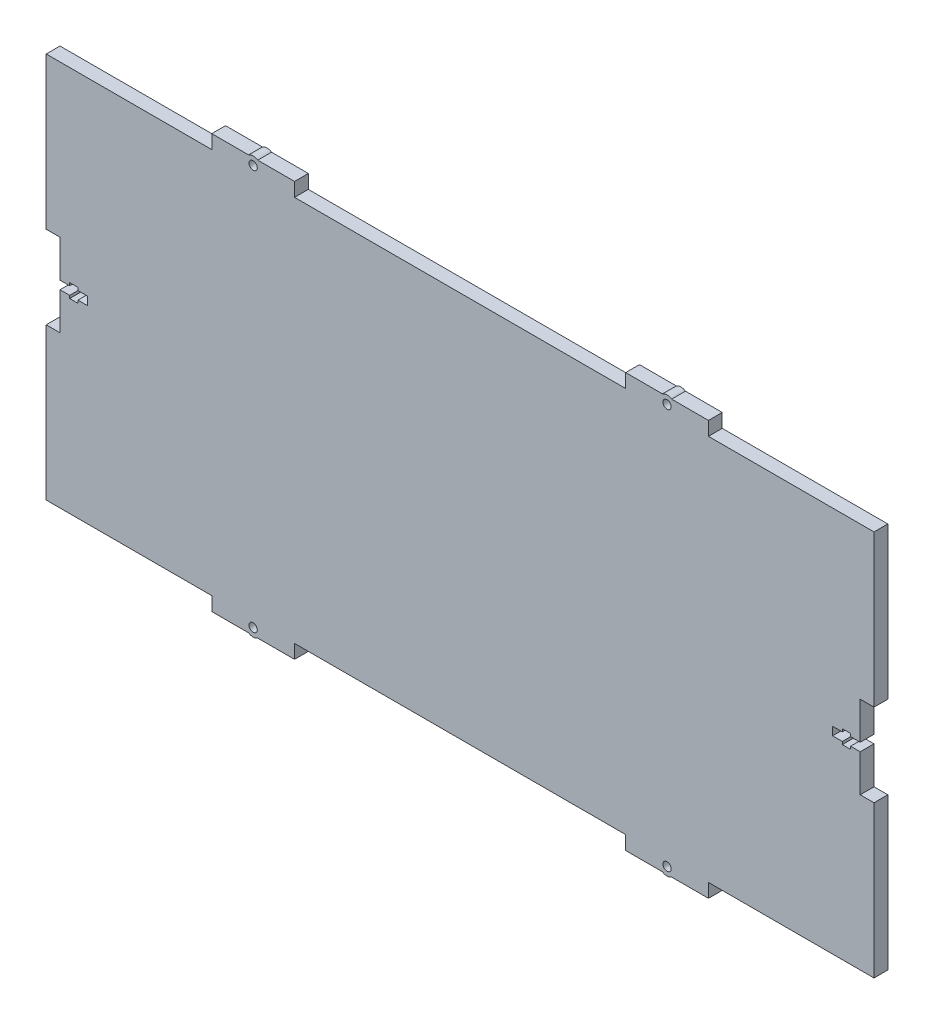
SolidWorks part; units mm, degrees
ref_plane "Plan de face" through (0, 0, 0) normal (0, 0, 1) x (1, 0, 0)
ref_plane "Plan de dessus" through (0, 0, 0) normal (0, 1, 0) x (1, 0, 0)
ref_plane "Plan de droite" through (0, 0, 0) normal (1, 0, 0) x (0, 0, -1)
sketch "Esquisse1" plane through (0, 0, 0) normal (0, 0, 1) x (1, 0, 0)
  line L4 (-160.6231, -51.1462) -> (-105.6231, -51.1462)
  line L5 (-160.6231, -51.1462) -> (-160.6231, 88.8538)
  line L6 (-160.6231, 88.8538) -> (-105.6231, 88.8538)
  line L7 (129.3769, -51.1462) -> (129.3769, 88.8538)
  line L8 (74.3769, -51.1462) -> (74.3769, -56.1462)
  line L10 (74.3769, -56.1462) -> (61.0352, -56.1462)
  line L11 (57.7186, -56.1462) -> (44.3769, -56.1462)
  line L12 (44.3769, -51.1462) -> (44.3769, -56.1462)
  line L13 (-75.6231, -51.1462) -> (-75.6231, -56.1462)
  line L14 (-89.1231, -56.1462) -> (-75.6231, -56.1462)
  line L15 (74.3769, -51.1462) -> (129.3769, -51.1462)
  line L16 (-105.6231, -56.1462) -> (-92.1231, -56.1462)
  line L17 (-105.6231, -51.1462) -> (-105.6231, -56.1462)
  line L19 (74.3769, 93.8538) -> (60.8769, 93.8538)
  line L20 (57.8769, 93.8538) -> (44.3769, 93.8538)
  line L21 (44.3769, 93.8538) -> (44.3769, 88.8538)
  line L22 (-75.6231, 93.8538) -> (-75.6231, 88.8538)
  line L23 (-89.1231, 93.8538) -> (-75.6231, 93.8538)
  line L24 (-15.6231, 104.2463) -> (-15.6231, -104.3766) construction
  line L25 (-105.6231, 93.8538) -> (-92.1231, 93.8538)
  line L26 (-105.6231, 93.8538) -> (-105.6231, 88.8538)
  line L27 (-196.6289, 18.8538) -> (196.6984, 18.8538) construction
  line L28 (74.3769, 93.8538) -> (74.3769, 88.8538)
  line L29 (74.3769, 88.8538) -> (129.3769, 88.8538)
  line L30 (-75.6231, 88.8538) -> (44.3769, 88.8538)
  line L31 (-75.6231, -51.1462) -> (44.3769, -51.1462)
  circle A1 centre (-90.6231, 91.3538) radius 1.5
  arc A2 (-88.9648, 93.8538) -> (-92.2814, 93.8538) centre (-90.6231, 91.3538) ccw
  arc A4 (57.7186, 93.8538) -> (61.0352, 93.8538) centre (59.3769, 91.3538) cw
  circle A6 centre (59.3769, 91.3538) radius 1.5
  arc A8 (57.7186, -56.1462) -> (61.0352, -56.1462) centre (59.3769, -53.6462) ccw
  circle A9 centre (59.3769, -53.6462) radius 1.5
  arc A10 (-88.9648, -56.1462) -> (-92.2814, -56.1462) centre (-90.6231, -53.6462) cw
  circle A11 centre (-90.6231, -53.6462) radius 1.5
  dimension "D1" = 140
extrude "Boss.-Extru.2" add sketch "Esquisse1" along normal blind 5
sketch "Esquisse2" plane through (-160.6231, 0, 0) normal (-1, 0, 0) x (0, 0, 1)
  line L4 (0, 88.8538) -> (0, -51.1462)
  line L5 (0, -51.1462) -> (5, -51.1462)
  line L6 (5, -51.1462) -> (5, 88.8538)
  line L7 (5, 88.8538) -> (0, 88.8538)
  line L8 (0, 88.8538) -> (0, -51.1462)
  line L9 (0, -51.1462) -> (5, -51.1462)
  line L10 (5, -51.1462) -> (5, 88.8538)
  line L11 (5, 88.8538) -> (0, 88.8538)
  dimension "D1" = 0
extrude "Boss.-Extru.3" add sketch "Esquisse2" along normal blind 5
sketch "Esquisse3" plane through (129.3769, 0, 0) normal (1, 0, 0) x (0, 0, -1)
  line L4 (0, -51.1462) -> (0, 88.8538)
  line L5 (0, 88.8538) -> (-5, 88.8538)
  line L6 (-5, 88.8538) -> (-5, -51.1462)
  line L7 (-5, -51.1462) -> (0, -51.1462)
  line L8 (0, -51.1462) -> (0, 88.8538)
  line L9 (0, 88.8538) -> (-5, 88.8538)
  line L10 (-5, 88.8538) -> (-5, -51.1462)
  line L11 (-5, -51.1462) -> (0, -51.1462)
  dimension "D1" = 0
extrude "Boss.-Extru.4" add sketch "Esquisse3" along normal blind 5
sketch "Esquisse4" plane through (0, 0, 5) normal (0, 0, 1) x (1, 0, 0)
  line L0 (-165.6231, -51.1462) -> (-165.6231, 88.8538) construction
  line L1 (-165.6231, 3.8538) -> (-160.6231, 3.8538)
  line L2 (-165.6231, 3.8538) -> (-165.6231, 33.8538)
  line L3 (-165.6231, 33.8538) -> (-160.6231, 33.8538)
  line L4 (-160.6231, 3.8538) -> (-160.6231, 33.8538)
  line L5 (-165.6231, 3.8538) -> (-160.6231, 3.8538) construction
  line L6 (-160.6231, 18.8538) -> (-95.5696, 18.8538) construction
  line L7 (-15.6231, 95.8351) -> (-15.6231, -101.4966) construction
  line L8 (-150.6231, 20.3538) -> (-160.6231, 20.3538)
  line L9 (-150.6231, 20.3538) -> (-150.6231, 17.3538)
  line L10 (-150.6231, 17.3538) -> (-160.6231, 17.3538)
  line L11 (-160.6231, 20.3538) -> (-160.6231, 17.3538)
  line L12 (-150.6231, 20.3538) -> (-160.6231, 17.3538) construction
  line L13 (-150.6231, 17.3538) -> (-160.6231, 20.3538) construction
  line L14 (-157.1231, 21.3538) -> (-154.1231, 21.3538)
  line L15 (-157.1231, 21.3538) -> (-157.1231, 16.3538)
  line L16 (-157.1231, 16.3538) -> (-154.1231, 16.3538)
  line L17 (-154.1231, 21.3538) -> (-154.1231, 16.3538)
  line L18 (-157.1231, 21.3538) -> (-154.1231, 16.3538) construction
  line L19 (-157.1231, 16.3538) -> (-154.1231, 21.3538) construction
  line L20 (119.3769, 17.3538) -> (129.3769, 17.3538)
  line L21 (129.3769, 20.3538) -> (129.3769, 17.3538)
  line L22 (119.3769, 20.3538) -> (129.3769, 20.3538)
  line L23 (119.3769, 20.3538) -> (119.3769, 17.3538)
  line L24 (125.8769, 16.3538) -> (122.8769, 16.3538)
  line L25 (122.8769, 21.3538) -> (122.8769, 16.3538)
  line L26 (125.8769, 21.3538) -> (122.8769, 21.3538)
  line L27 (125.8769, 21.3538) -> (125.8769, 16.3538)
  line L28 (134.3769, 33.8538) -> (129.3769, 33.8538)
  line L29 (129.3769, 3.8538) -> (129.3769, 33.8538)
  line L30 (134.3769, 3.8538) -> (129.3769, 3.8538)
  line L31 (134.3769, 3.8538) -> (134.3769, 33.8538)
  point P12 (-155.6231, 18.8538)
  point P13 (-155.6231, 18.8538)
  line M24 (134.3769, -51.1462) -> (134.3769, 88.8538)
  line M38 (-165.6231, 88.8538) -> (-165.6231, -51.1462)
  dimension "D1" = 3
  dimension "D2" = 10
  dimension "D3" = 3
  dimension "D4" = 5
extrude "Enlèv. mat.-Extru.1" cut sketch "Esquisse4" against normal blind 10 contours L1 L4 L3 M38 | L15 L8 L4 L10 | L17 L8 L15 L10 | L17 L14 L15 L8 | L17 L10 L15 L16 | L8 L17 L10 L9 | L30 L28 L29 L21 M24 | L22 L27 L20 L21 | L27 L22 L25 L20 | L27 L26 L25 L22 | L27 L20 L25 L24 | L25 L22 L23 L20
sketch "Esquisse5" plane through (0, 0, 5) normal (0, 0, 1) x (1, 0, 0)
  line L0 (-15.6231, 88.8538) -> (-15.6231, -51.1462) construction
  line L1 (-75.6231, 88.8538) -> (44.3769, 88.8538) construction
  line L2 (-75.6231, -51.1462) -> (44.3769, -51.1462) construction
  circle A0 centre (-15.6231, -31.1462) radius 10
  dimension "D1" = 20
  dimension "D2" = 20
